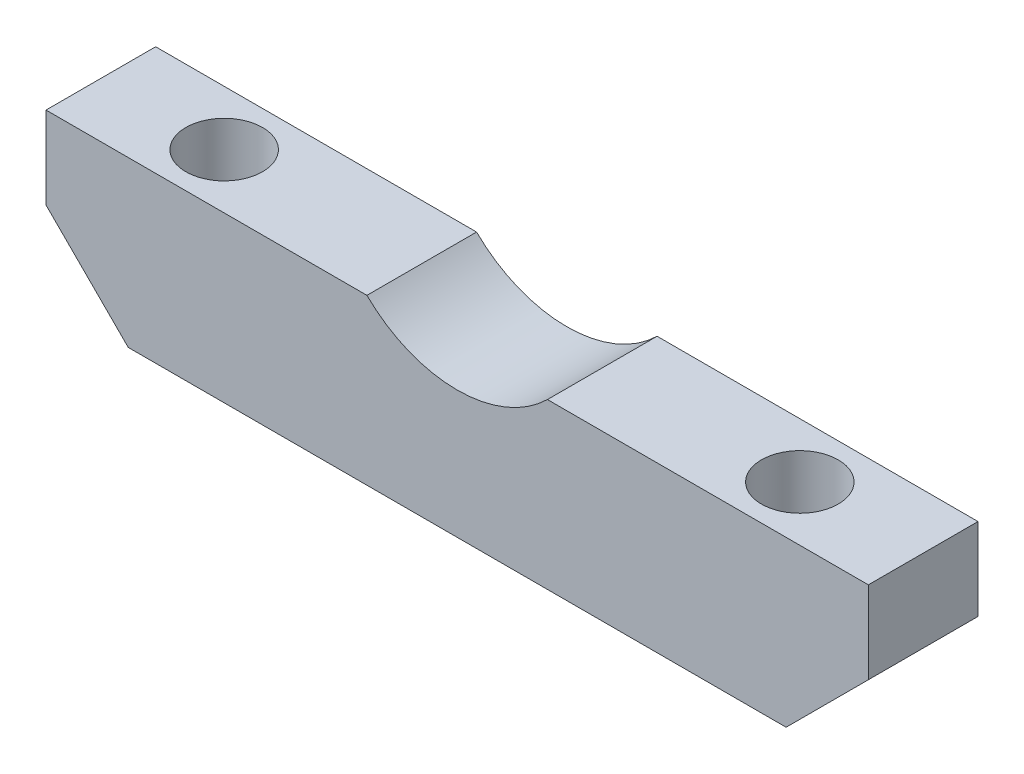
SolidWorks part; units mm, degrees
material "尼龙 101"
ref_plane "前视基准面" through (0, 0, 0) normal (0, 0, 1) x (1, 0, 0)
ref_plane "上视基准面" through (0, 0, 0) normal (0, 1, 0) x (1, 0, 0)
ref_plane "右视基准面" through (0, 0, 0) normal (1, 0, 0) x (0, 0, -1)
sketch "草图1" plane through (0, 0, 0) normal (0, 0, 1) x (1, 0, 0)
  line L1 (-15, -6.5) -> (15, -6.5)
  line L2 (-15, -6.5) -> (-15, 6.5)
  line L3 (-15, 6.5) -> (15, 6.5)
  line L4 (15, -6.5) -> (15, 6.5)
  line L5 (-15, -6.5) -> (15, 6.5) construction
  line L6 (-15, 6.5) -> (15, -6.5) construction
  point P0 (0, 0)
  dimension "D1" = 13
  dimension "D2" = 30
extrude "凸台-拉伸1" add sketch "草图1" along normal blind 4
sketch "草图3" plane through (0, 0, 4) normal (0, 0, 1) x (1, 0, 0)
  circle A0 centre (0, 9.8541) radius 4.7
  dimension "D1" = 9.4
extrude "切除-拉伸2" cut sketch "草图3" against normal blind 10
sketch "草图5" plane through (0, 0, 4) normal (0, 0, 1) x (1, 0, 0)
  line L0 (0, 9.8541) -> (0, -0.6459) construction
  circle A0 centre (0, 9.8541) radius 10.5 construction
  point P5 (0, -0.6459)
  dimension "D1" = 21
hole_wizard "M2 螺纹孔1" positions "3D草图2" profile "草图6" tap size "M2" standard "GB"
sketch3d "3D草图2"
  point P0 (0, -0.6459, 4)
sketch "草图6" plane through (0, -0.6459, 4) normal (1, 0, 0) x (0, -1, 0)
  line L0 (0, 0) -> (0, 6.4807)
  line L1 (0, 6.4807) -> (0.8, 6)
  line L2 (0.8, 6) -> (0.8, 0)
  line L5 (0.8, 0) -> (0, 0)
  line L10 (0, 6.4807) -> (-0.8, 6) construction
  line L11 (0, -6.35) -> (0, 107.95) construction
  dimension "螺纹孔钻头直径" = 1.6
  dimension "螺纹孔钻头深度" = 6
  dimension "导头角度" = 118
cosmetic thread "孔螺蚊线1" parameters "D1"=4, "D2"=2
sketch "草图7" plane through (0, 0, 4) normal (0, 0, 1) x (1, 0, 0)
  line L1 (-15, -6.5) -> (15, -6.5)
  line L2 (-15, -6.5) -> (-15, 0.5)
  line L3 (-15, 0.5) -> (15, 0.5)
  line L4 (15, -6.5) -> (15, 0.5)
  line L5 (15, -6.5) -> (15, 6.5) construction
  dimension "D1" = 7
  dimension "D2" = 30
extrude "切除-拉伸3" cut sketch "草图7" against normal blind 10
sketch "草图8" plane through (0, 0.5, 0) normal (0, -1, 0) x (1, 0, 0)
  line L0 (-15, 0) -> (-15, 4) construction
  circle A0 centre (-10.5, 2) radius 1.4
  point P0 (-10.5, 2)
  dimension "D2" = 2.8
  dimension "D1" = 4.5
chamfer "倒角1" distance 3 angle 45 2 edges at (15, 0.5, 2) (-15, 0.5, 2)
extrude "切除-拉伸4" cut sketch "草图8" against normal blind 10
mirror "镜向1" about plane through (0, 0, 0) normal (1, 0, 0) of "切除-拉伸4"
